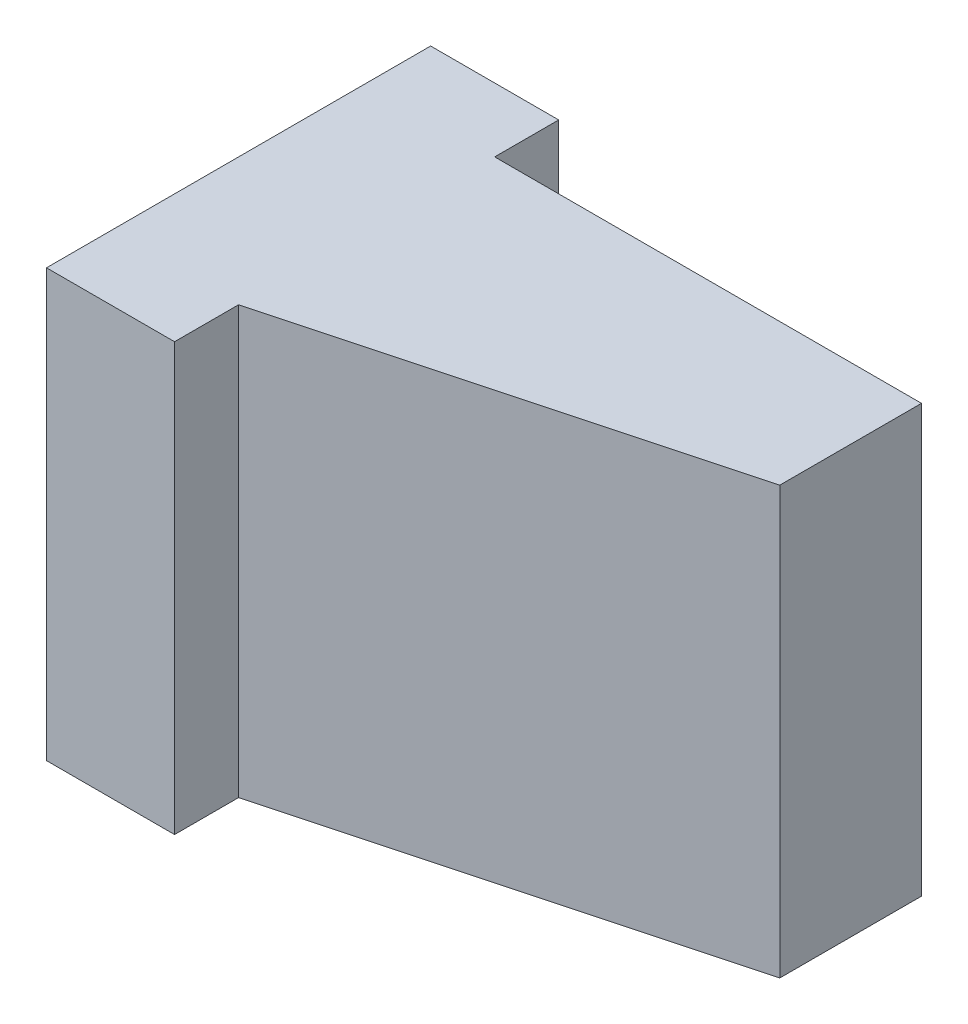
SolidWorks part; units mm, degrees
ref_plane "Ebene vorne" through (0, 0, 0) normal (0, 0, 1) x (1, 0, 0)
ref_plane "Ebene oben" through (0, 0, 0) normal (0, 1, 0) x (1, 0, 0)
ref_plane "Ebene rechts" through (0, 0, 0) normal (1, 0, 0) x (0, 0, -1)
sketch "Skizze1" plane through (0, 0, 0) normal (0, 1, 0) x (1, 0, 0)
  line L10 (-16.813, -2.6179) -> (-26.813, -5.2974)
  line L12 (-26.813, 0.7026) -> (-26.813, 2.2026)
  line L13 (-26.813, 2.2026) -> (-29.813, 2.2026)
  line L14 (-29.813, 2.2026) -> (-29.813, -6.7974)
  line L15 (-29.813, -6.7974) -> (-26.813, -6.7974)
  line L16 (-26.813, -6.7974) -> (-26.813, -5.2974)
  line L17 (-26.813, 0.7026) -> (-16.813, 0.7026)
  line L18 (-16.813, 0.7026) -> (-16.813, -2.6179)
  dimension "D1" = 165
  dimension "D2" = 1.5
  dimension "D3" = 1.5
  dimension "D4" = 10
  dimension "D5" = 3
  dimension "D6" = 3
  dimension "D7" = 9
extrude "Aufsatz-Linear austragen1" add sketch "Skizze1" along normal blind 10
sketch "Skizze2" plane through (-29.813, 0, 0) normal (-1, 0, 0) x (0, 0, 1)
  line L0 (-2.2026, 10) -> (6.7974, 0) construction
  circle A0 centre (2.2974, 5) radius 1.25
  dimension "D1" = 2.5
extrude "Aufsatz-Linear austragen2" add sketch "Skizze2" along normal blind 2
ref_plane "Ebene9" through (-16.813, 10, -0.7026) normal (-1, 0, 0) x (0, 0, 1)
